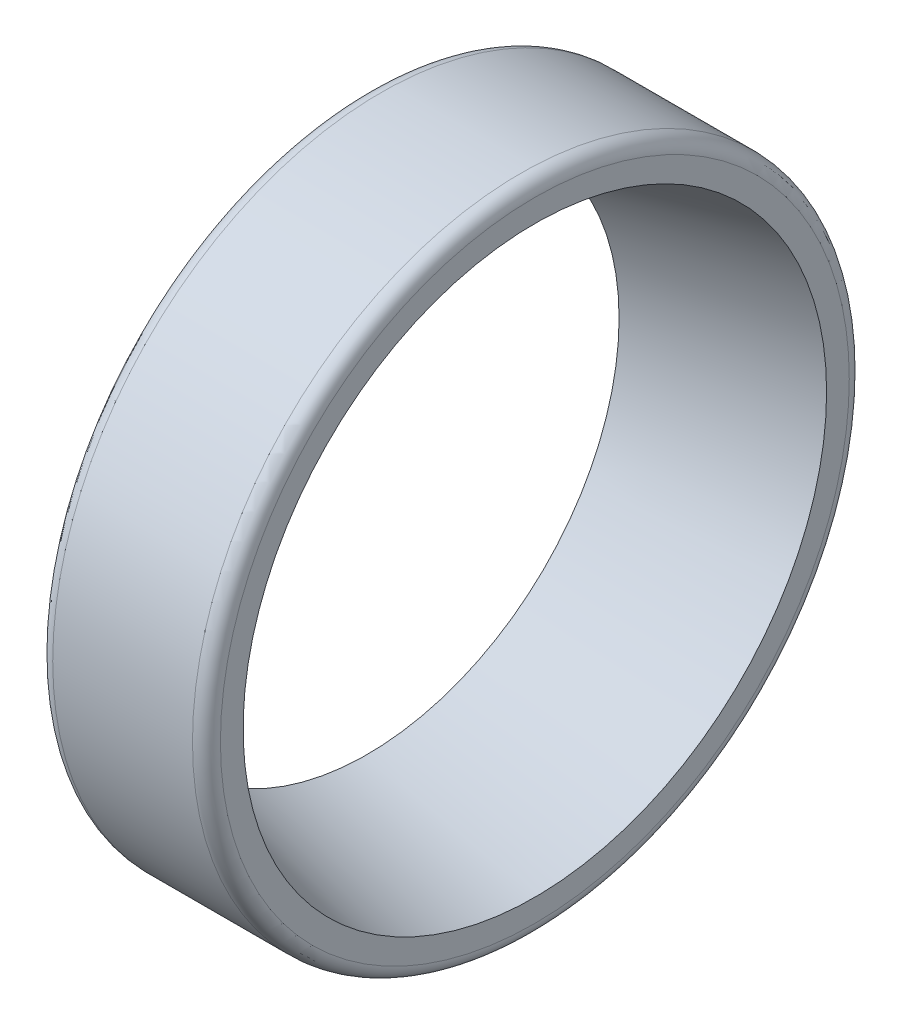
SolidWorks part; units mm, degrees
material "SUJ2"
ref_plane "Front Plane" through (0, 0, 0) normal (0, 0, 1) x (1, 0, 0)
ref_plane "Top Plane" through (0, 0, 0) normal (0, 1, 0) x (1, 0, 0)
ref_plane "Right Plane" through (0, 0, 0) normal (1, 0, 0) x (0, 0, -1)
sketch "ｽｹｯﾁ1" plane through (0, 0, 0) normal (0, 0, 1) x (1, 0, 0)
  line L0 (0, 22.5) -> (0, 18.0284)
  line L1 (0, 18.0284) -> (12, 20.8774)
  line L2 (12, 20.8774) -> (12, 22.5)
  line L3 (11, 23.5) -> (1, 23.5)
  line L4 (-0.0013, 0) -> (12.0013, 0) construction
  arc A0 (1, 23.5) -> (0, 22.5) centre (1, 22.5) ccw
  arc A1 (12, 22.5) -> (11, 23.5) centre (11, 22.5) ccw
revolve "回転1" add sketch "ｽｹｯﾁ1" angle 360 about L4
